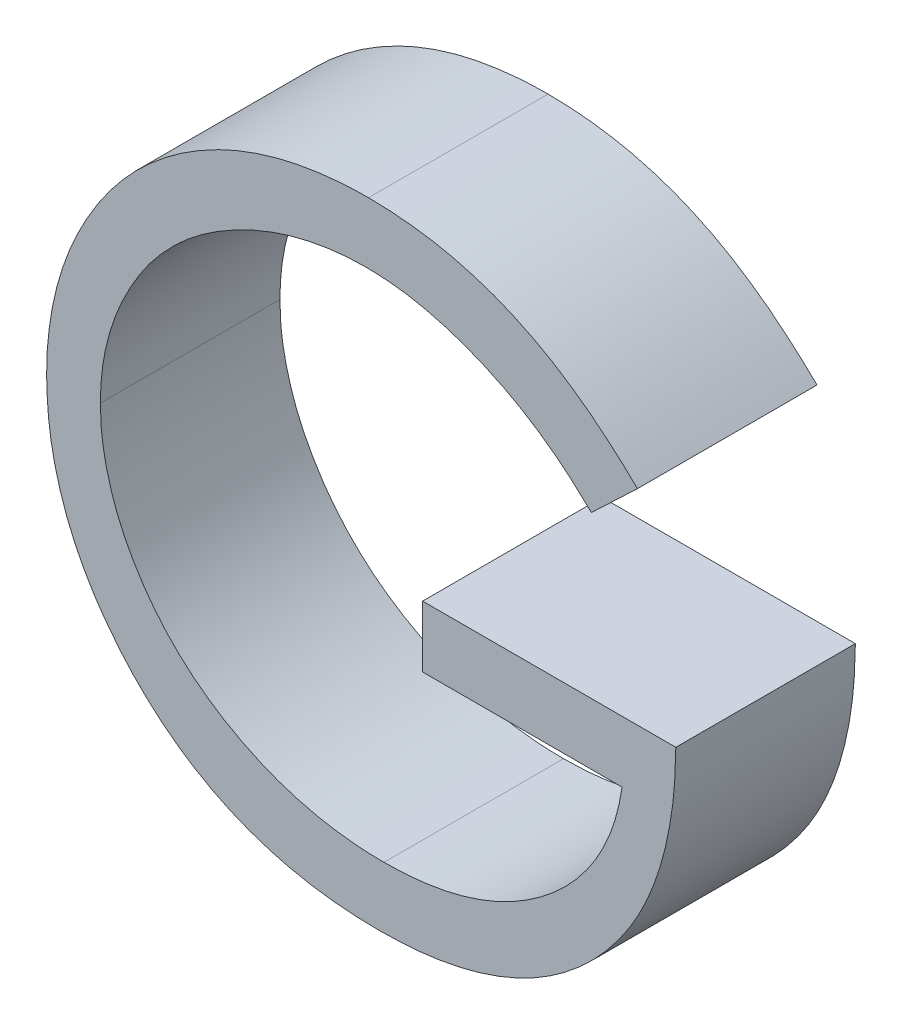
SolidWorks part; units mm, degrees
ref_plane "Plan de face" through (0, 0, 0) normal (0, 0, 1) x (1, 0, 0)
ref_plane "Plan de dessus" through (0, 0, 0) normal (0, 1, 0) x (1, 0, 0)
ref_plane "Plan de droite" through (0, 0, 0) normal (1, 0, 0) x (0, 0, -1)
sketch "Esquisse1" plane through (0, 0, 0) normal (0, 0, 1) x (1, 0, 0)
  text T0 "G" font "Century Gothic" height 5
extrude "Boss.-Extru.1" add sketch "Esquisse1" along normal blind 1.5
